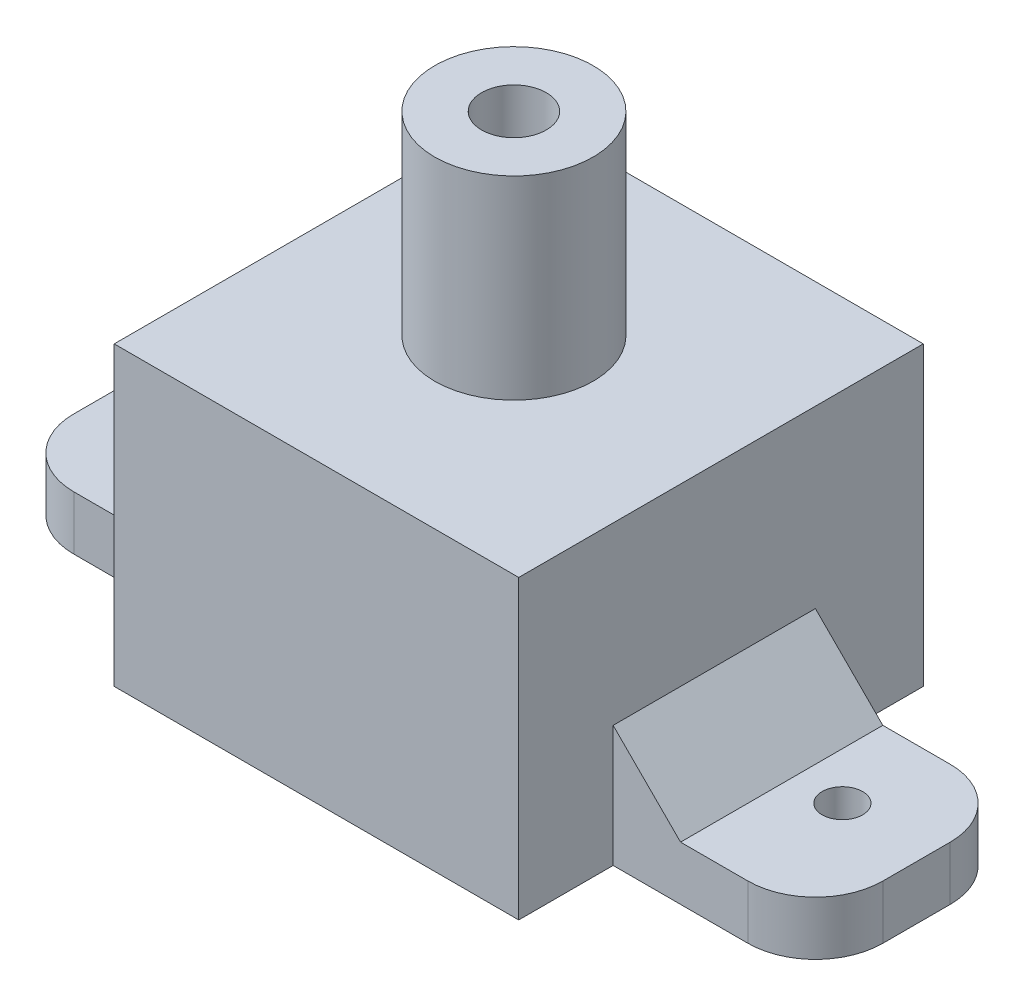
SolidWorks part; units mm, degrees
ref_plane "Спереди" through (0, 0, 0) normal (0, 0, 1) x (1, 0, 0)
ref_plane "Сверху" through (0, 0, 0) normal (0, 1, 0) x (1, 0, 0)
ref_plane "Справа" through (0, 0, 0) normal (1, 0, 0) x (0, 0, -1)
other "Configuration Table"
sketch "Эскиз1" plane through (0, 0, 0) normal (0, 1, 0) x (1, 0, 0)
  line L1 (-14.2865, 14.6433) -> (15.7135, 14.6433)
  line L2 (-14.2865, 14.6433) -> (-14.2865, -15.3567)
  line L3 (-14.2865, -15.3567) -> (15.7135, -15.3567)
  line L4 (15.7135, 14.6433) -> (15.7135, -15.3567)
  dimension "D1" = 30
  dimension "D2" = 30
extrude "высота " add sketch "Эскиз1" along normal blind 22
sketch "Эскиз2" plane through (0, 22, 0) normal (0, 1, 0) x (1, 0, 0)
  circle A0 centre (0, 0) radius 5.875
  dimension "D1" = 11.75
sketch "Эскиз3" plane through (0, 0, 0) normal (0, 0, 1) x (1, 0, 0)
  line L0 (0, 49.97) -> (0, -1.7648) construction
extrude "Бобышка-Вытянуть2" add sketch "Эскиз2" along normal blind 14.4 contours A0
sketch "Эскиз4" plane through (0, 36.4, 0) normal (0, 1, 0) x (1, 0, 0)
  circle A0 centre (0, 0) radius 2.4
  dimension "D1" = 4.8
sketch "Эскиз5" plane through (0, 0, 0) normal (0, -1, 0) x (1, 0, 0)
  line L0 (15.7135, 15.3567) -> (15.7135, -14.6433) construction
  line L1 (15.7135, 8.3567) -> (25.7135, 8.3567)
  line L2 (15.7135, 8.3567) -> (15.7135, -6.6433)
  line L3 (15.7135, -6.6433) -> (25.7135, -6.6433)
  line L4 (30.7135, 3.3567) -> (30.7135, -1.6433)
  line L5 (15.7135, -14.6433) -> (-14.2865, -14.6433) construction
  line L6 (0, 0) -> (0, -14.6433) construction
  line L12 (-14.2865, -14.6433) -> (-14.2865, 15.3567) construction
  line L13 (-14.2865, 8.3567) -> (-24.2865, 8.3567)
  line L14 (-14.2865, 8.3567) -> (-14.2865, -6.6433)
  line L15 (-14.2865, -6.6433) -> (-24.2865, -6.6433)
  line L16 (-29.2865, 3.3567) -> (-29.2865, -1.6433)
  arc A0 (-29.2865, 3.3567) -> (-24.2865, 8.3567) centre (-24.2865, 3.3567) cw
  arc A1 (-24.2865, -6.6433) -> (-29.2865, -1.6433) centre (-24.2865, -1.6433) cw
  arc A2 (30.7135, 3.3567) -> (25.7135, 8.3567) centre (25.7135, 3.3567) ccw
  arc A3 (30.7135, -1.6433) -> (25.7135, -6.6433) centre (25.7135, -1.6433) cw
  point P19 (-29.2865, 8.3567)
  point P22 (-29.2865, -6.6433)
  point P25 (30.7135, 8.3567)
  point P28 (30.7135, -6.6433)
  dimension "D7" = 5
  dimension "D8" = 5
  dimension "D9" = 5
  dimension "D10" = 5
  dimension "D1" = 15
  dimension "D2" = 15
  dimension "D3" = 8
  dimension "D4" = 15
  dimension "D5" = 15
  dimension "D6" = 8
extrude "Бобышка-Вытянуть4" add sketch "Эскиз5" against normal blind 4
sketch "Эскиз6" plane through (0, 4, 0) normal (0, 1, 0) x (1, 0, 0)
  line L0 (30.7135, 1.6433) -> (30.7135, -3.3567) construction
  line L1 (15.7135, 6.6433) -> (25.7135, 6.6433) construction
  line L2 (-24.2865, 6.6433) -> (-14.2865, 6.6433) construction
  line L3 (-29.2865, -3.3567) -> (-29.2865, 1.6433) construction
  circle A0 centre (24.2135, 0.1433) radius 1.5
  circle A1 centre (-22.7865, 0.1433) radius 1.5
  dimension "D1" = 3
  dimension "D4" = 3
  dimension "D2" = 6.5
  dimension "D3" = 6.5
  dimension "D5" = 6.5
  dimension "D6" = 6.5
extrude "Вырез-Вытянуть2" cut sketch "Эскиз6" against normal through all both and the other way through all contours A1 | A0
chamfer "Фаска2" distance 5 angle 45 1 edges at (15.7135, 4, 0.8567)
chamfer "Фаска3" distance 5 angle 45 1 edges at (-14.2865, 4, 0.8567)
extrude "Вырез-Вытянуть3" cut sketch "Эскиз4" against normal blind 8
